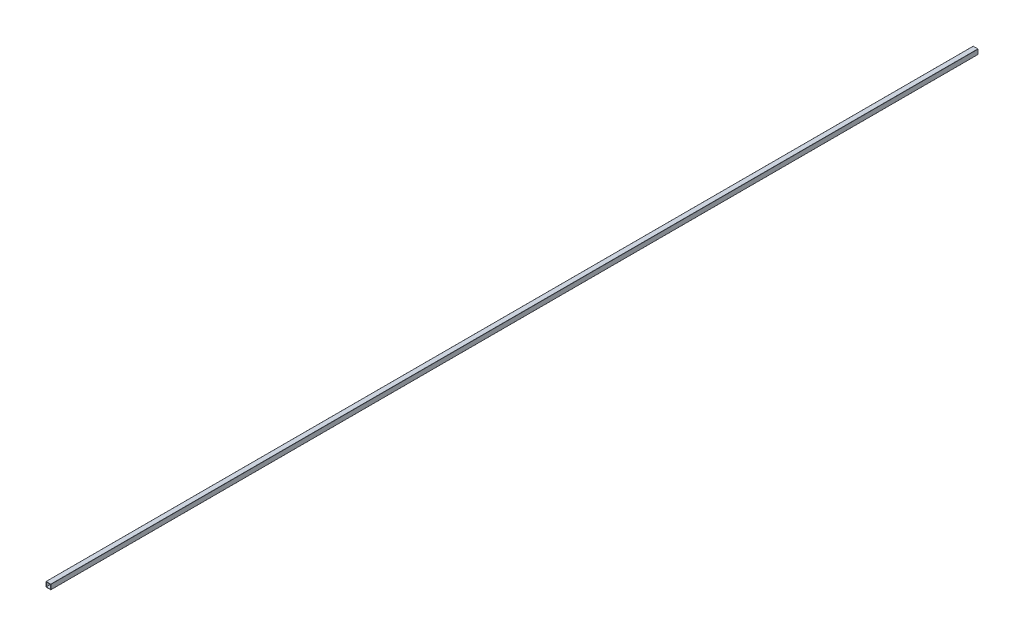
SolidWorks part; units mm, degrees
material "AISI 1035 Acero (SS)"
ref_plane "Alzado" through (0, 0, 0) normal (0, 0, 1) x (1, 0, 0)
ref_plane "Planta" through (0, 0, 0) normal (0, 1, 0) x (1, 0, 0)
ref_plane "Vista lateral" through (0, 0, 0) normal (1, 0, 0) x (0, 0, -1)
sketch "Croquis1" plane through (0, 0, 0) normal (0, 0, 1) x (1, 0, 0)
  line L1 (-14.85, -15.85) -> (14.85, -15.85)
  line L2 (-15.85, -14.85) -> (-15.85, 14.85)
  line L3 (-14.85, 15.85) -> (14.85, 15.85)
  line L4 (15.85, -14.85) -> (15.85, 14.85)
  line L5 (-15.85, -15.85) -> (15.85, 15.85) construction
  line L6 (-15.85, 15.85) -> (15.85, -15.85) construction
  line L7 (-13.96, -13.96) -> (-13.96, 13.96)
  line L8 (-13.96, 13.96) -> (13.96, 13.96)
  line L9 (13.96, -13.96) -> (13.96, 13.96)
  line L10 (-13.96, -13.96) -> (13.96, -13.96)
  arc A0 (14.85, 15.85) -> (15.85, 14.85) centre (14.85, 14.85) cw
  arc A1 (14.85, -15.85) -> (15.85, -14.85) centre (14.85, -14.85) ccw
  arc A2 (-15.85, -14.85) -> (-14.85, -15.85) centre (-14.85, -14.85) ccw
  arc A3 (-15.85, 14.85) -> (-14.85, 15.85) centre (-14.85, 14.85) cw
  arc A4 (-13.96, 13.96) -> (-13.96, 13.96) centre (-13.96, 13.96) cw
  arc A5 (13.96, 13.96) -> (13.96, 13.96) centre (13.96, 13.96) cw
  arc A6 (13.96, -13.96) -> (13.96, -13.96) centre (13.96, -13.96) ccw
  arc A7 (-13.96, -13.96) -> (-13.96, -13.96) centre (-13.96, -13.96) ccw
  point P0 (0, 0)
  dimension "D2" = 1
  dimension "D1" = 31.7
  dimension "D3" = 1.89
extrude "Saliente-Extruir1" add sketch "Croquis1" along normal blind 6000
